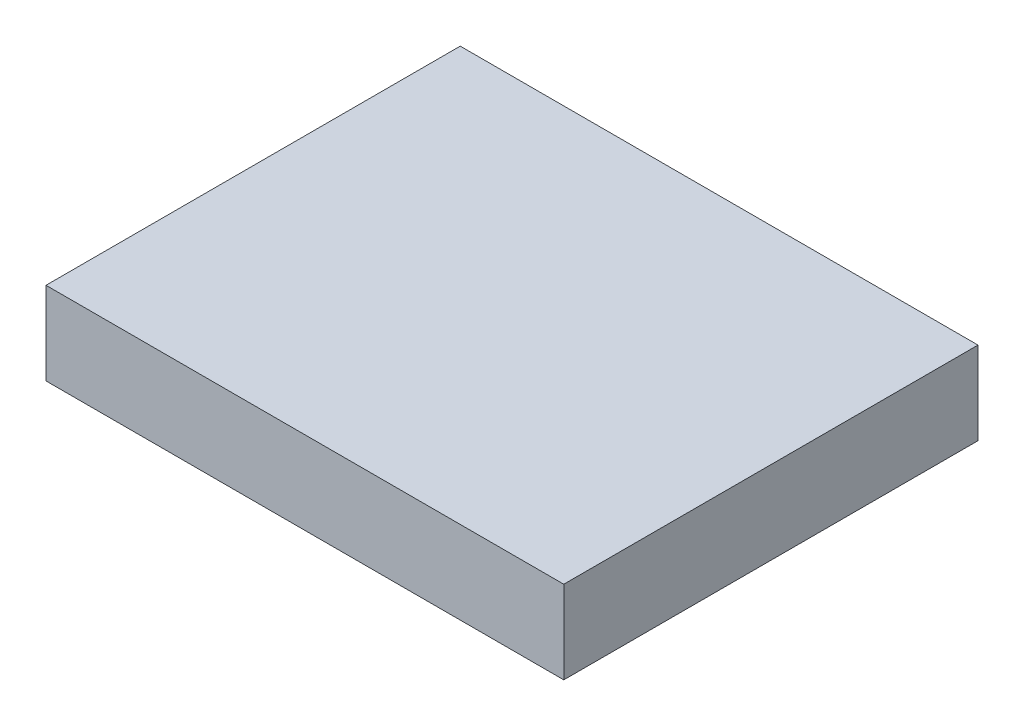
SolidWorks part; units mm, degrees
ref_plane "前视基准面" through (0, 0, 0) normal (0, 0, 1) x (1, 0, 0)
ref_plane "上视基准面" through (0, 0, 0) normal (0, 1, 0) x (1, 0, 0)
ref_plane "右视基准面" through (0, 0, 0) normal (1, 0, 0) x (0, 0, -1)
sketch "草图1" plane through (0, 0, 0) normal (0, 1, 0) x (1, 0, 0)
  line L1 (0, 0) -> (25, 0)
  line L2 (0, 0) -> (0, -20)
  line L3 (0, -20) -> (25, -20)
  line L4 (25, 0) -> (25, -20)
  dimension "D1" = 25
  dimension "D2" = 20
extrude "凸台-拉伸1" add sketch "草图1" along normal blind 4
